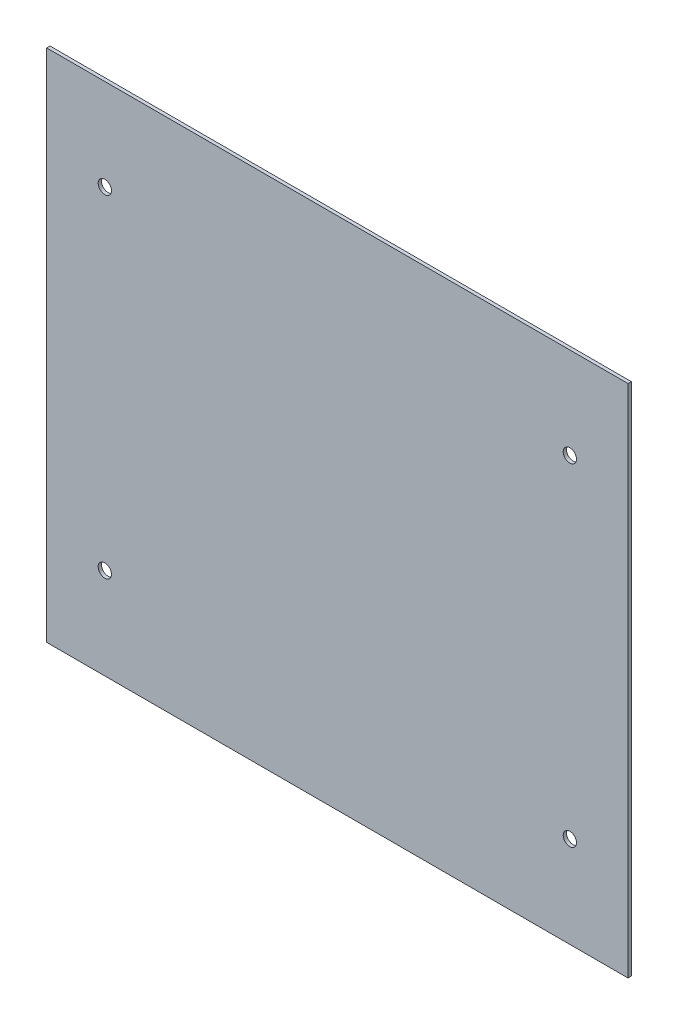
SolidWorks part; units mm, degrees
ref_plane "Front Plane" through (0, 0, 0) normal (0, 0, 1) x (1, 0, 0)
ref_plane "Top Plane" through (0, 0, 0) normal (0, 1, 0) x (1, 0, 0)
ref_plane "Right Plane" through (0, 0, 0) normal (1, 0, 0) x (0, 0, -1)
sketch "Sketch1" plane through (0, 0, 0) normal (0, 0, 1) x (1, 0, 0)
  line L1 (175, -155) -> (-175, -155)
  line L2 (175, -155) -> (175, 155)
  line L3 (175, 155) -> (-175, 155)
  line L4 (-175, -155) -> (-175, 155)
  line L5 (175, -155) -> (-175, 155) construction
  line L6 (175, 155) -> (-175, -155) construction
  point P0 (0, 0)
  dimension "D1" = 350
  dimension "D2" = 310
extrude "Boss-Extrude1" add sketch "Sketch1" along normal blind 2
sketch "Sketch2" plane through (0, 0, 2) normal (0, 0, 1) x (1, 0, 0)
  line L0 (175, 155) -> (-175, 155) construction
  line L1 (-175, 155) -> (-175, -155) construction
  line L2 (0, 155) -> (0, -147.5554) construction
  line L3 (175, 0) -> (-163.6381, 0) construction
  line L4 (175, -155) -> (175, 155) construction
  circle A0 centre (-140, 100) radius 4
  circle A1 centre (-140, -100) radius 4
  circle A2 centre (140, -100) radius 4
  circle A3 centre (140, 100) radius 4
  dimension "D1" = 8
  dimension "D2" = 55
  dimension "D3" = 35
extrude "Cut-Extrude1" cut sketch "Sketch2" against normal through all
